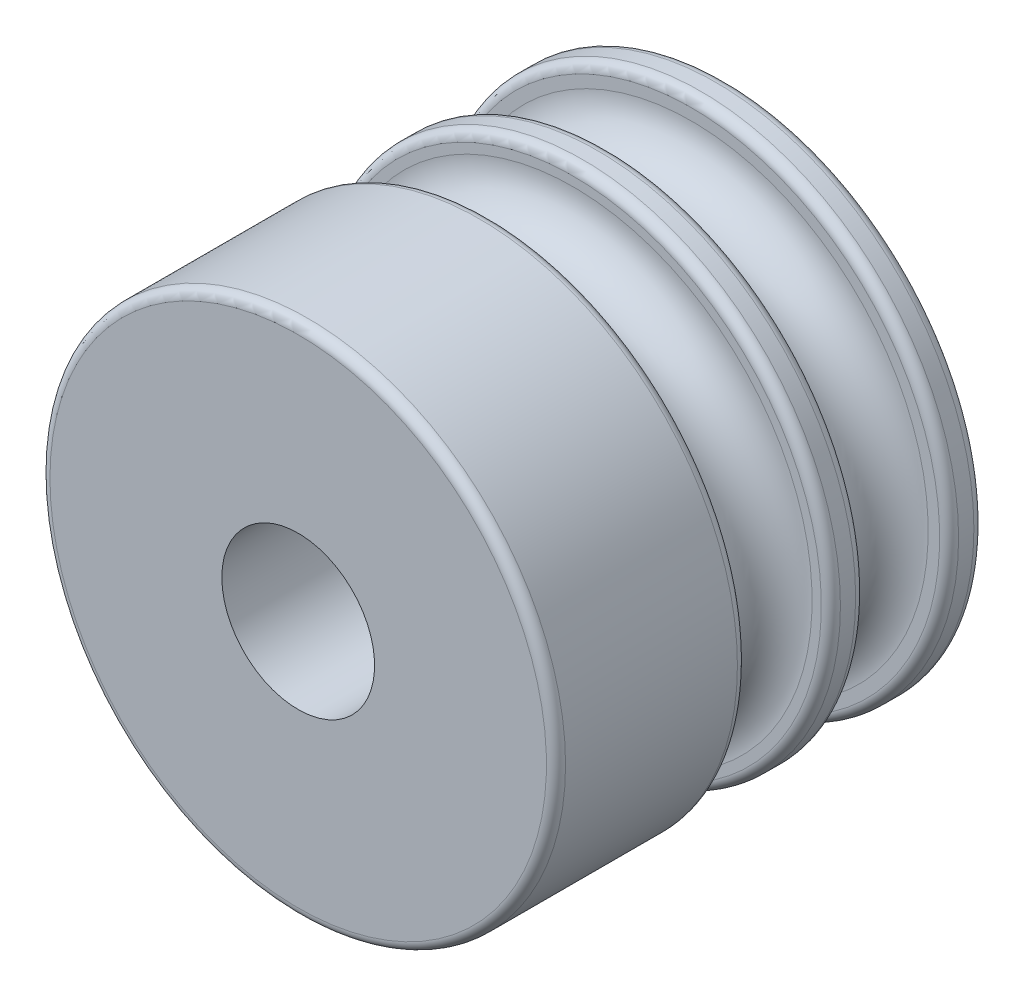
SolidWorks part; units mm, degrees
ref_plane "Front Plane" through (0, 0, 0) normal (0, 0, 1) x (1, 0, 0)
ref_plane "Top Plane" through (0, 0, 0) normal (0, 1, 0) x (1, 0, 0)
ref_plane "Right Plane" through (0, 0, 0) normal (1, 0, 0) x (0, 0, -1)
sketch "Sketch1" plane through (0, 0, 0) normal (0, 1, 0) x (1, 0, 0)
  line L0 (-56.5563, 55.2783) -> (-56.5563, -14.7217) construction
  line L1 (-44.0513, 12.4531) -> (-43.5563, 12.4531)
  line L2 (-43.0563, 2.9531) -> (-43.0563, 11.9531)
  line L3 (-43.5563, 2.4531) -> (-52.5563, 2.4531)
  line L5 (-44.0394, 16.8475) -> (-43.5563, 16.8475)
  line L6 (-52.5563, 24.8438) -> (-52.5563, 2.4531)
  line L11 (-43.0563, 23.5355) -> (-43.0563, 24.3355)
  line L13 (-45.8534, 24.8438) -> (-52.5563, 24.8438)
  line L14 (-43.5562, 24.8438) -> (-45.8534, 24.8438)
  line L15 (-44.156, 18.6438) -> (-43.5563, 18.6438)
  line L16 (-43.0563, 17.3475) -> (-43.0563, 18.1438)
  line L17 (-43.5562, 23.0438) -> (-44.156, 23.0438)
  arc A0 (-43.5563, 2.4531) -> (-43.0563, 2.9531) centre (-43.5563, 2.9531) ccw
  arc A1 (-43.5563, 12.4531) -> (-43.0563, 11.9531) centre (-43.5563, 11.9531) cw
  arc A2 (-44.0394, 16.8475) -> (-44.0513, 12.4531) centre (-44.156, 14.6506) ccw
  arc A3 (-44.156, 23.0438) -> (-44.156, 18.6438) centre (-44.156, 20.8438) ccw
  arc A4 (-43.0563, 24.3355) -> (-43.5562, 24.8438) centre (-43.5562, 24.3438) ccw
  arc A5 (-43.5563, 16.8475) -> (-43.0563, 17.3475) centre (-43.5563, 17.3475) ccw
  arc A6 (-43.5563, 18.6438) -> (-43.0563, 18.1438) centre (-43.5563, 18.1438) cw
  arc A7 (-43.0563, 23.5355) -> (-43.5562, 23.0438) centre (-43.5562, 23.5438) cw
  dimension "D11" = 4.4
  dimension "D12" = 4.4
  dimension "D4" = 0.5
  dimension "D8" = 13.5
  dimension "D2" = 70
  dimension "D3" = 4
  dimension "D5" = 1.8
  dimension "D6" = 9
  dimension "D7" = 13.5
  dimension "D9" = 13.5
  dimension "D13" = 1.8
revolve "Revolve1" add sketch "Sketch1" angle 360 about L0
